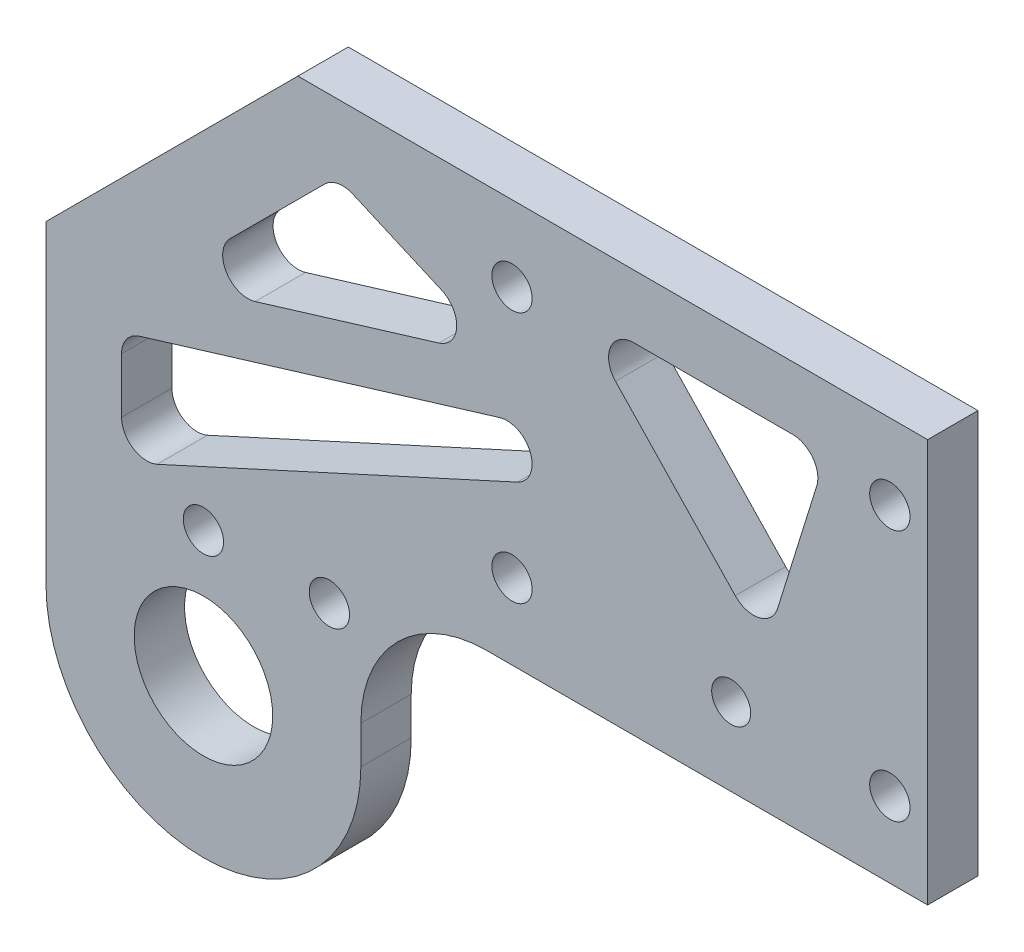
SolidWorks part; units mm, degrees
ref_plane "前视基准面" through (0, 0, 0) normal (0, 0, 1) x (1, 0, 0)
ref_plane "上视基准面" through (0, 0, 0) normal (0, 1, 0) x (1, 0, 0)
ref_plane "右视基准面" through (0, 0, 0) normal (1, 0, 0) x (0, 0, -1)
ref_plane "基准面1" through (0, 0, 0) normal (0, 0, -1) x (-1, 0, 0)
sketch "草图1" plane through (0, 0, 0) normal (0, 0, -1) x (-1, 0, 0)
  line L0 (12.5, 0) -> (12.5, 15)
  line L1 (-17.5, 45) -> (-57.5, 45)
  line L2 (-57.5, 45) -> (-57.5, 13)
  line L3 (-57.5, 13) -> (-22.5, 13)
  line L4 (-12.5, 3) -> (-12.5, 0)
  line L5 (12.5, 15) -> (12.5, 45)
  line L6 (12.5, 45) -> (-17.5, 45)
  circle A0 centre (-54.5, 19) radius 1.6
  circle A1 centre (-24.5, 19) radius 1.6
  circle A2 centre (-24.5, 39) radius 1.6
  circle A3 centre (-54.5, 39) radius 1.6
  circle A4 centre (0, 0) radius 6.075
  arc A6 (-22.5, 13) -> (-12.5, 3) centre (-22.5, 3) cw
  arc A7 (-12.5, 0) -> (12.5, 0) centre (0, 0) ccw
extrude "凸台-拉伸1" add sketch "草图1" against normal blind 4
sketch "草图2" plane through (0, 0, 0) normal (0, 0, -1) x (-1, 0, 0)
  circle A0 centre (0, 10) radius 1.6
  circle A1 centre (0, 0) radius 6.075 construction
  dimension "D1" = 3.2
  dimension "D2" = 10
extrude "切除-拉伸1" cut sketch "草图2" against normal up to next
sketch "草图3" plane through (0, 0, 4) normal (0, 0, 1) x (1, 0, 0)
  circle A0 centre (10, 10) radius 1.6
  circle A1 centre (0, 10) radius 1.6 construction
  dimension "D1" = 3.2
  dimension "D2" = 10
extrude "切除-拉伸2" cut sketch "草图3" against normal up to next
sketch "草图4" plane through (0, 0, 4) normal (0, 0, 1) x (1, 0, 0)
  line L4 (57.5, 45) -> (57.5, 13) construction
  line L5 (57.5, 13) -> (22.5, 13) construction
  circle A0 centre (41.9036, 19.1683) radius 1.55
  dimension "D1" = 3.1
  dimension "D2" = 15.5964
  dimension "D3" = 6.1683
extrude "切除-拉伸3" cut sketch "草图4" against normal up to next
sketch "草图5" plane through (0, 0, 4) normal (0, 0, 1) x (1, 0, 0)
  circle A0 centre (0, 0) radius 5.5
  circle A1 centre (0, 0) radius 6.075
  dimension "D1" = 11
extrude "凸台-拉伸2" add sketch "草图5" against normal blind 4
chamfer "倒角1" distance 20 angle 45 1 edges at (-12.5, 45, 2)
sketch "草图6" plane through (0, 0, 4) normal (0, 0, 1) x (1, 0, 0)
  line L0 (9.6345, 38.6492) -> (2.1136, 31.1283)
  line L1 (4.1101, 27.8008) -> (18.692, 32.2386)
  line L2 (18.91, 35.9849) -> (11.849, 39.0679)
  line L3 (32.7175, 36.6209) -> (42.2273, 26.6332)
  line L4 (45.5854, 27.4182) -> (48.6929, 37.4058)
  line L5 (46.7832, 40) -> (34.1659, 40)
  line L6 (-6.5, 18.9086) -> (-6.5, 14.5402)
  line L7 (-3.6685, 12.7212) -> (24.9279, 25.7927)
  line L8 (23.5142, 29.5251) -> (-5.0823, 20.822)
  line L9 (7.5, 45) -> (-12.5, 25) construction
  line L10 (-12.5, 0) -> (-12.5, 25) construction
  line L11 (7.5, 45) -> (57.5, 45) construction
  circle A0 centre (0, 10) radius 1.6 construction
  circle A1 centre (24.5, 39) radius 1.6 construction
  circle A2 centre (41.9036, 19.1683) radius 1.55 construction
  circle A3 centre (54.5, 39) radius 1.6 construction
  circle A4 centre (24.5, 19) radius 1.6 construction
  arc A5 (48.6929, 37.4058) -> (46.7832, 40) centre (46.7832, 38) ccw
  arc A6 (42.2273, 26.6332) -> (45.5854, 27.4182) centre (43.6757, 28.0123) ccw
  arc A7 (32.7175, 36.6209) -> (34.1659, 40) centre (34.1659, 38) cw
  arc A8 (24.9279, 25.7927) -> (23.5142, 29.5251) centre (24.0965, 27.6117) ccw
  arc A9 (18.692, 32.2386) -> (18.91, 35.9849) centre (18.1097, 34.152) ccw
  arc A10 (-6.5, 14.5402) -> (-3.6685, 12.7212) centre (-4.5, 14.5402) ccw
  arc A11 (-6.5, 18.9086) -> (-5.0823, 20.822) centre (-4.5, 18.9086) cw
  arc A12 (2.1136, 31.1283) -> (4.1101, 27.8008) centre (3.5278, 29.7141) ccw
  arc A13 (9.6345, 38.6492) -> (11.849, 39.0679) centre (11.0487, 37.235) cw
  point P30 (49.5, 40)
  point P33 (44.5743, 24.1683)
  point P36 (29.5, 40)
  point P47 (-3.5432, 25.4715)
  point P50 (10.599, 39.6137)
  dimension "D4" = 4
  dimension "D8" = 5
  dimension "D11" = 6
  dimension "D12" = 2
  dimension "D1" = 6
  dimension "D2" = 6
  dimension "D3" = 4
  dimension "D5" = 20
  dimension "D6" = 5
  dimension "D7" = 5
  dimension "D9" = 5
  dimension "D10" = 5
extrude "切除-拉伸4" cut sketch "草图6" against normal blind 10
